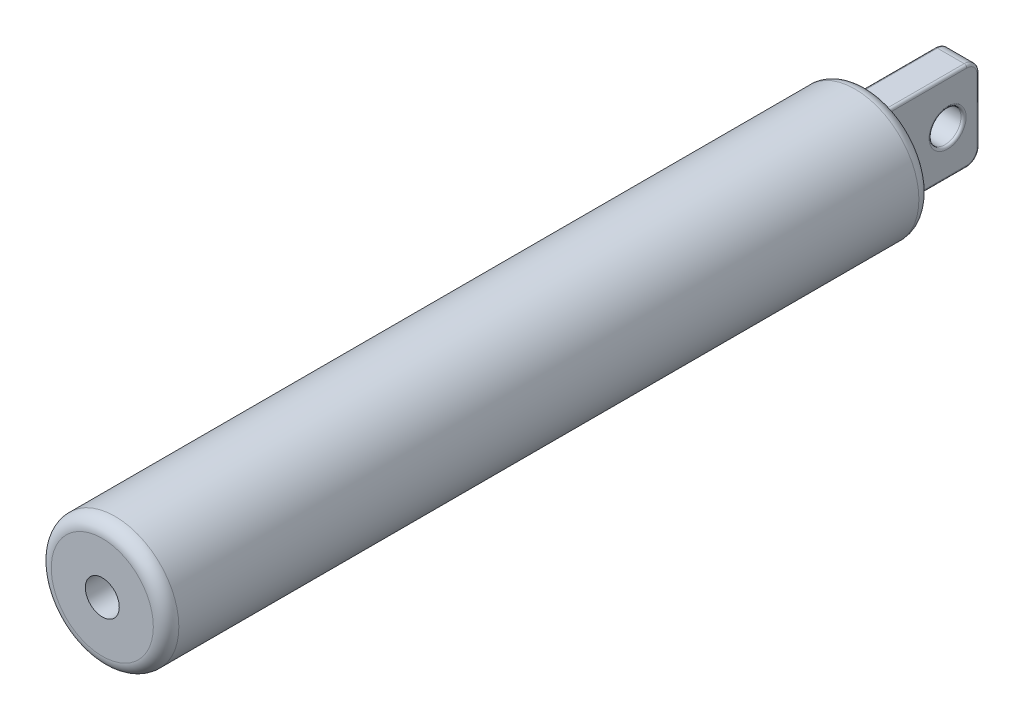
SolidWorks part; units mm, degrees
material "6061-T6 (SS)"
ref_plane "Front" through (0, 0, 0) normal (0, 0, 1) x (1, 0, 0)
ref_plane "Top" through (0, 0, 0) normal (0, 1, 0) x (1, 0, 0)
ref_plane "Right" through (0, 0, 0) normal (1, 0, 0) x (0, 0, -1)
sketch "Sketch1" plane through (0, 0, 0) normal (0, 0, 1) x (1, 0, 0)
  circle A0 centre (0, 0) radius 12.7
  dimension "D1" = 25.4
extrude "Extrude1" add sketch "Sketch1" along normal blind 152.4
hole_wizard "1/4 Clearance Hole1" positions "Sketch3" profile "Sketch2" hole size "1/4" standard "Ansi Inch"
sketch "Sketch3" plane through (0, 0, 152.4) normal (0, 0, 1) x (1, 0, 0)
  point P0 (0, 0)
sketch "Sketch2" plane through (0, 0, 152.4) normal (1, 0, 0) x (0, -1, 0)
  line L0 (0, 0) -> (0, 151.2548)
  line L1 (0, 151.2548) -> (3.3782, 149.225)
  line L2 (3.3782, 149.225) -> (3.3782, 0)
  line L5 (3.3782, 0) -> (0, 0)
  line L10 (0, 151.2548) -> (-3.3782, 149.225) construction
  line L11 (0, -6.35) -> (0, 107.95) construction
  dimension "Hole Dia." = 6.7564
  dimension "Hole Depth" = 149.225
  dimension "Drill Angle" = 118
sketch "Sketch4" plane through (0, 0, 0) normal (0, 0, -1) x (-1, 0, 0)
  line L1 (-3.175, -8.89) -> (3.175, -8.89)
  line L2 (-3.175, -8.89) -> (-3.175, 8.89)
  line L3 (-3.175, 8.89) -> (3.175, 8.89)
  line L4 (3.175, -8.89) -> (3.175, 8.89)
  line L5 (-3.175, -8.89) -> (3.175, 8.89) construction
  line L6 (-3.175, 8.89) -> (3.175, -8.89) construction
  point P0 (0, 0)
  dimension "D1" = 6.35
  dimension "D2" = 17.78
extrude "Extrude2" add sketch "Sketch4" along normal blind 19.05
sketch "Sketch5" plane through (0, 0, 0) normal (1, 0, 0) x (0, 0, -1)
  line L0 (12.7, 8.89) -> (12.7, -8.89) construction
  line L1 (19.05, 8.89) -> (0, 8.89) construction
  line L2 (19.05, -8.89) -> (0, -8.89) construction
  line L3 (19.05, 8.89) -> (19.05, -8.89) construction
  circle A0 centre (12.7, 0) radius 3.175
  dimension "D1" = 6.35
  dimension "D2" = 6.35
extrude "Extrude3" cut sketch "Sketch5" against normal mid plane 25.4
fillet "Fillet1" radius 2.54 1 edges at (12.7, 0, 152.4)
fillet "Fillet2" radius 2.54 3 edges at (0, -8.89, -19.05) (0, 8.89, -19.05) (12.7, 0, 0)
fillet "Fillet3" radius 0.508 16 edges at (0, 8.89, 0) (0, -8.89, 0) (-3.175, 8.1461, -18.3061) (-3.175, 8.89, -8.255) (-3.175, 0, 0) (-3.175, -8.89, -8.255) (-3.175, -8.1461, -18.3061) (-3.175, 0, -19.05) (3.175, 0, 0) (3.175, 8.89, -8.255) (3.175, 8.1461, -18.3061) (3.175, 0, -19.05) (3.175, -8.1461, -18.3061) (3.175, -8.89, -8.255) (-3.175, 0, -15.875) (3.175, 0, -9.525)
